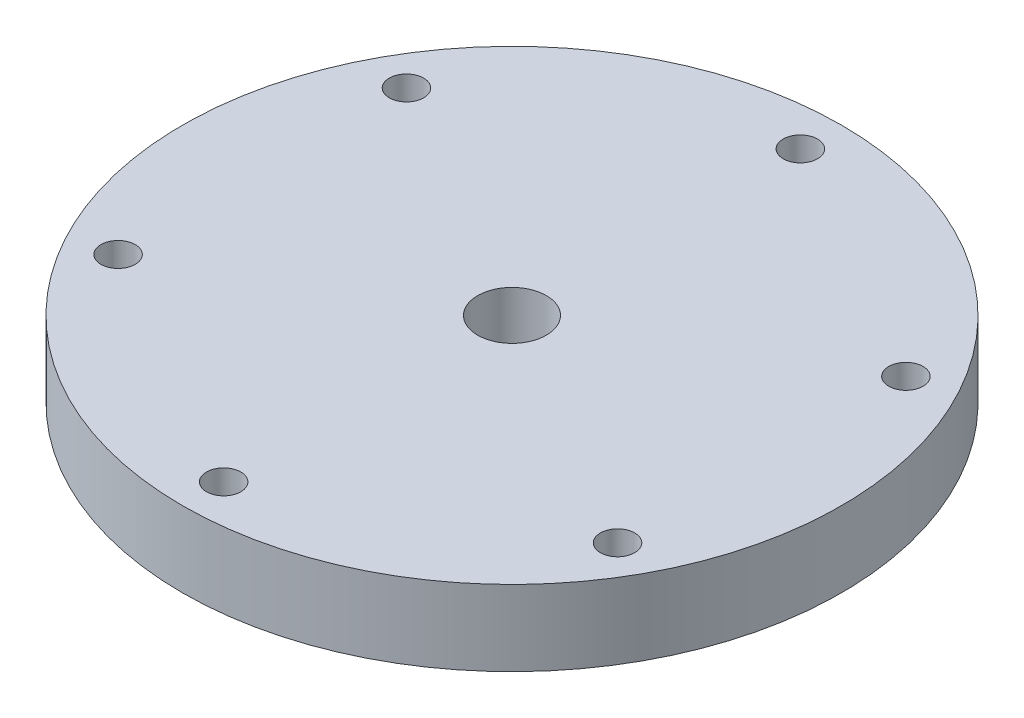
SolidWorks part; units mm, degrees
ref_plane "前视基准面" through (0, 0, 0) normal (0, 0, 1) x (1, 0, 0)
ref_plane "上视基准面" through (0, 0, 0) normal (0, 1, 0) x (1, 0, 0)
ref_plane "右视基准面" through (0, 0, 0) normal (1, 0, 0) x (0, 0, -1)
other "Configuration Table"
sketch "草图1" plane through (0, 0, 0) normal (0, 1, 0) x (1, 0, 0)
  circle A0 centre (0, 0) radius 24
  dimension "D1" = 48
extrude "凸台-拉伸1" add sketch "草图1" along normal mid plane 5.5
sketch "草图2" plane through (0, 2.75, 0) normal (0, 1, 0) x (1, 0, 0)
  circle A0 centre (0, 0) radius 21 construction
  point P4 (0, 21)
  dimension "D1" = 42
sketch "草图4" plane through (0, 2.75, 0) normal (0, 1, 0) x (1, 0, 0)
  circle A0 centre (0, 0) radius 2.5
  dimension "D1" = 5
extrude "切除-拉伸1" cut sketch "草图4" against normal blind 22
sketch "草图5" plane through (0, -2.75, 0) normal (0, -1, 0) x (1, 0, 0)
  line L1 (-9, 12) -> (9, 12)
  line L2 (-9, 12) -> (-9, -12)
  line L3 (-9, -12) -> (9, -12)
  line L4 (9, 12) -> (9, -12)
  line L5 (-9, 12) -> (9, -12) construction
  line L6 (-9, -12) -> (9, 12) construction
  circle A0 centre (-9, 12) radius 1.5
  circle A1 centre (9, 12) radius 1.5
  circle A2 centre (9, -12) radius 1.5
  circle A3 centre (-9, -12) radius 1.5
  point P0 (0, 0)
  dimension "D3" = 3
  dimension "D4" = 3
  dimension "D5" = 3
  dimension "D6" = 3
  dimension "D1" = 18
  dimension "D2" = 24
sketch "草图6" plane through (0, 2.75, 0) normal (0, 1, 0) x (1, 0, 0)
  circle A0 centre (0, 21) radius 1.25
  dimension "D1" = 2.5
extrude "切除-拉伸3" cut sketch "草图6" against normal blind 3
pattern_circular "阵列(圆周)1" count 6 every 60 about axis through (0, 0, 0) along (0, 1, 0) of "切除-拉伸3"
scale "缩放比例1" scale about centroid uniform scaling yes scale factor 1.5
